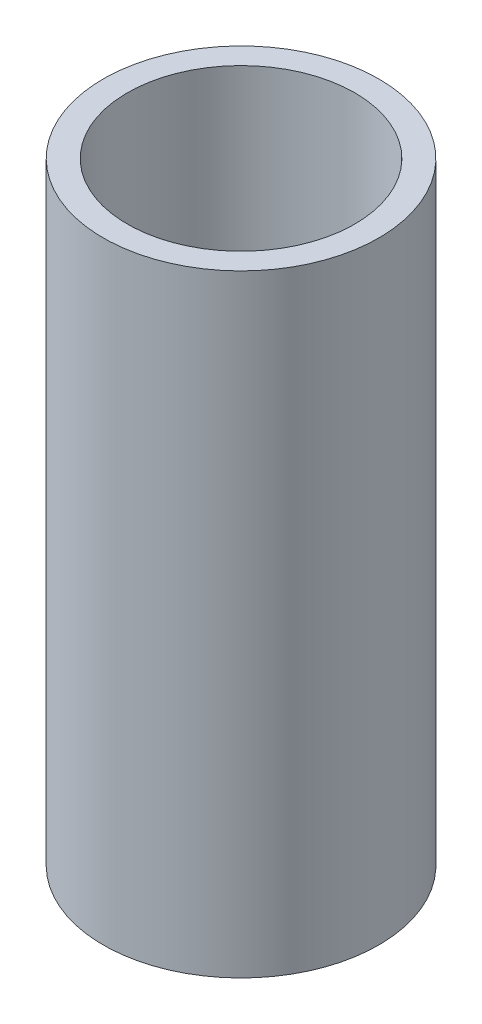
SolidWorks part; units mm, degrees
ref_plane "Płaszczyzna przednia" through (0, 0, 0) normal (0, 0, 1) x (1, 0, 0)
ref_plane "Płaszczyzna górna" through (0, 0, 0) normal (0, 1, 0) x (1, 0, 0)
ref_plane "Płaszczyzna prawa" through (0, 0, 0) normal (1, 0, 0) x (0, 0, -1)
sketch "Szkic1" plane through (0, 0, 0) normal (0, 0, 1) x (1, 0, 0)
  line L0 (0, 0) -> (0, 102.4) construction
  line L1 (-19.02, 100.113) -> (-19.02, 7.33)
  line L2 (-23.04, 100.113) -> (-23.04, -2.287)
  line L3 (-23.04, 100.113) -> (-19.02, 100.113)
  line L4 (-23.04, -2.287) -> (-17.02, -2.287)
  line L5 (-17.02, -2.287) -> (-9.51, -1.63)
  line L6 (-19.02, 7.33) -> (0, 7.33)
  line L9 (-9.51, -1.63) -> (0, -1.63)
  line L10 (0, -1.63) -> (0, 7.33)
  dimension "D1" = 19.02
  dimension "D2" = 23.04
  dimension "D3" = 102.4
  dimension "D4" = 5
  dimension "D5" = 8.96
  dimension "D6" = 9.51
revolve "Obrót1" add sketch "Szkic1" angle 360 about L0
